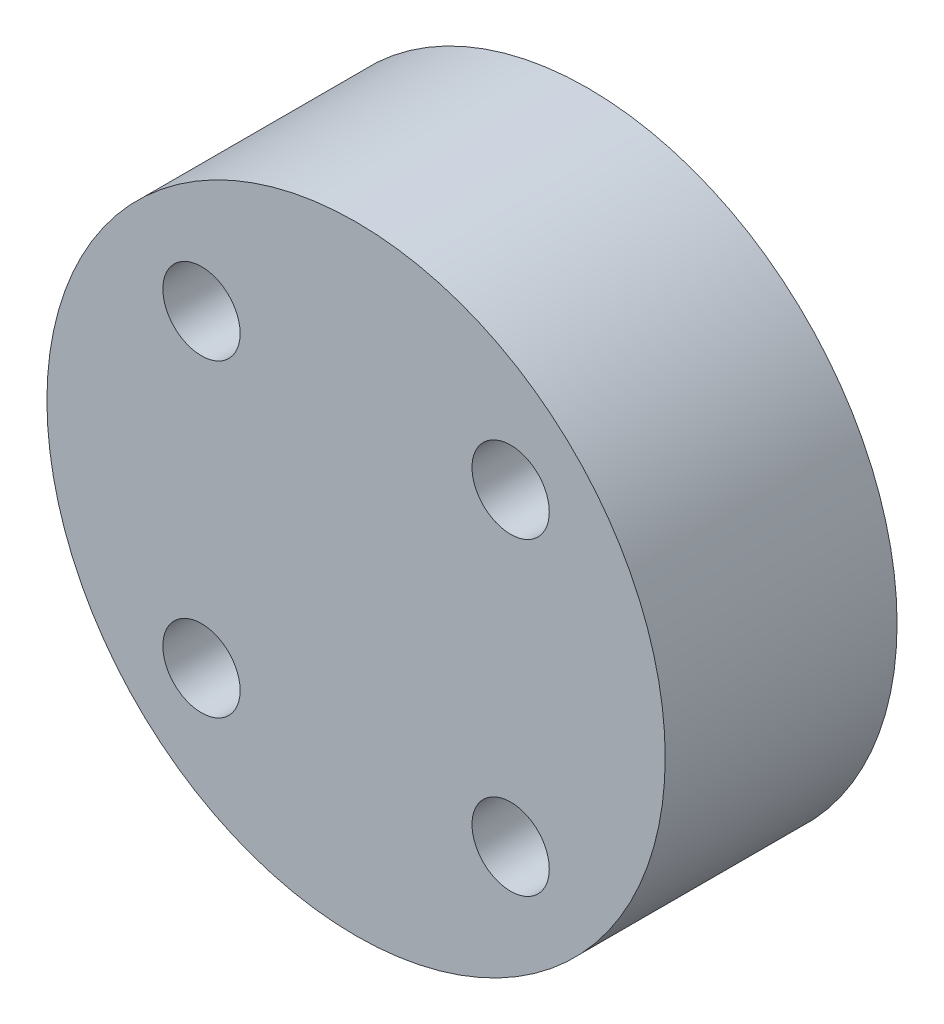
SolidWorks part; units mm, degrees
ref_plane "前视基准面" through (0, 0, 0) normal (0, 0, 1) x (1, 0, 0)
ref_plane "上视基准面" through (0, 0, 0) normal (0, 1, 0) x (1, 0, 0)
ref_plane "右视基准面" through (0, 0, 0) normal (1, 0, 0) x (0, 0, -1)
sketch "草图1" plane through (0, 0, 0) normal (0, 0, 1) x (1, 0, 0)
  circle A0 centre (0, 0) radius 20
  dimension "D1" = 40
extrude "凸台-拉伸1" add sketch "草图1" along normal blind 15
sketch "草图2" plane through (0, 0, 15) normal (0, 0, 1) x (1, 0, 0)
  line L0 (0, -8.25) -> (0, 8.25) construction
  line L1 (8.25, 0) -> (-8.25, 0) construction
  circle A0 centre (-10, 10) radius 2.5
  circle A1 centre (10, 10) radius 2.5
  circle A2 centre (10, -10) radius 2.5
  circle A3 centre (-10, -10) radius 2.5
  point P15 (0, 0)
  dimension "D1" = 10
  dimension "D2" = 10
  dimension "D3" = 4
extrude "切除-拉伸1" cut sketch "草图2" against normal through all
